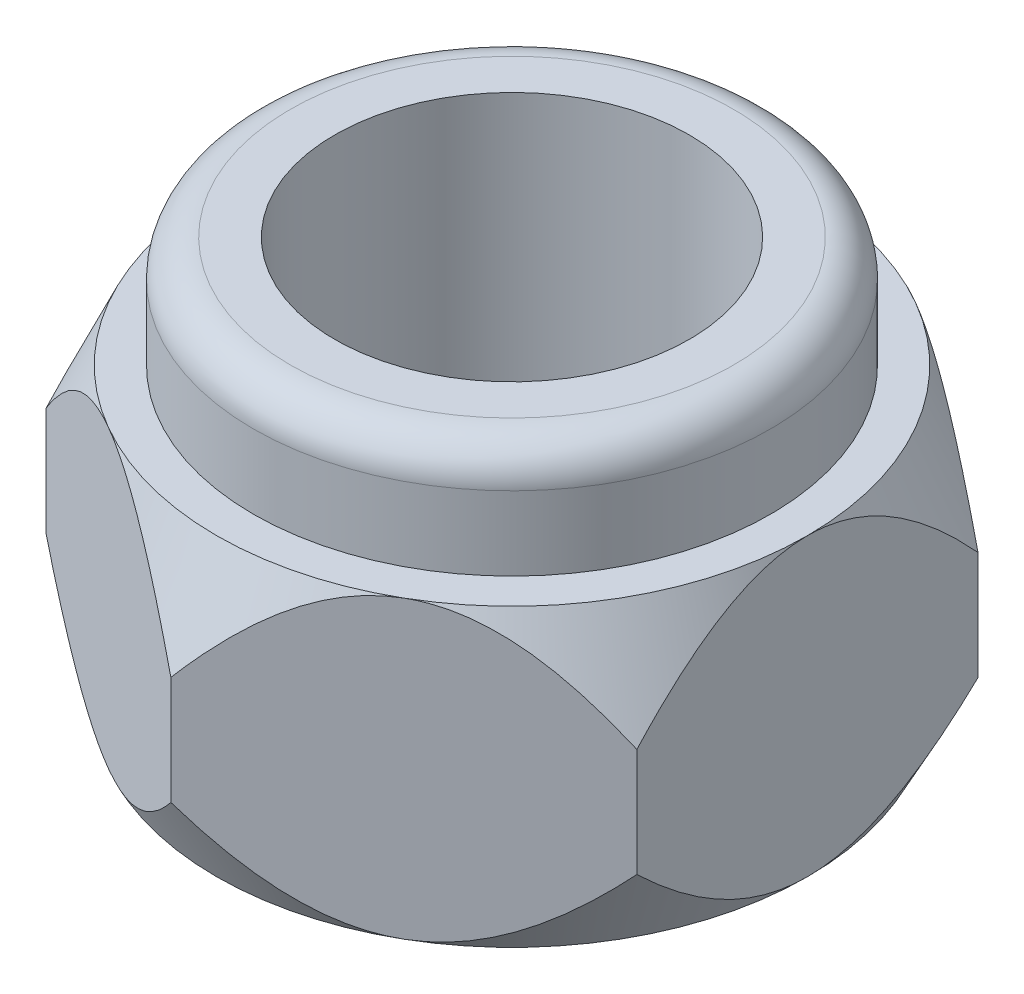
SolidWorks part; units mm, degrees
ref_plane "前视基准面" through (0, 0, 0) normal (0, 0, 1) x (1, 0, 0)
ref_plane "上视基准面" through (0, 0, 0) normal (0, 1, 0) x (1, 0, 0)
ref_plane "右视基准面" through (0, 0, 0) normal (1, 0, 0) x (0, 0, -1)
other "Configuration Table"
sketch "草图1" plane through (0, 0, 0) normal (0, 1, 0) x (1, 0, 0)
  line L1 (4, 2.3094) -> (0, 4.6188)
  line L2 (0, 4.6188) -> (-4, 2.3094)
  line L3 (-4, 2.3094) -> (-4, -2.3094)
  line L4 (-4, -2.3094) -> (0, -4.6188)
  line L5 (0, -4.6188) -> (4, -2.3094)
  line L6 (4, -2.3094) -> (4, 2.3094)
  circle A0 centre (0, 0) radius 4 construction
  dimension "D1" = 8
extrude "凸台-拉伸1" add sketch "草图1" along normal blind 4
sketch "草图2" plane through (0, 4, 0) normal (0, 1, 0) x (1, 0, 0)
  circle A0 centre (0, 0) radius 3.5
  dimension "D1" = 7
extrude "凸台-拉伸2" add sketch "草图2" along normal blind 1.5
fillet "圆角1" radius 0.5 1 edges at (0, 5.5, 3.5)
sketch "草图3" plane through (0, 0, 0) normal (0, -1, 0) x (1, 0, 0)
  circle A0 centre (0, 0) radius 2.4
  dimension "D1" = 4.8
extrude "切除-拉伸1" cut sketch "草图3" against normal through all
cosmetic thread "装饰螺纹线1" parameters "D2"=6
sketch "草图4" plane through (0, 0, 0) normal (0, 0, 1) x (1, 0, 0)
  line L0 (4.7086, 0) -> (4.7086, 1.3523)
  line L1 (0, 0) -> (4, 0) construction
  line L2 (4, 4) -> (4, 0) construction
  line L3 (4.7086, 1.3523) -> (4, 0)
  line L4 (4, 0) -> (4.7086, 0)
  line L5 (0, 0) -> (0, 0.8841) construction
  line L6 (0, 4) -> (0, 0) construction
  line L7 (4, 4) -> (4.7086, 4)
  line L8 (4.7086, 4) -> (4.7086, 2.4518)
  line L9 (4.7086, 2.4518) -> (4, 4)
revolve "切除-旋转1" cut sketch "草图4" angle 360 about L5
